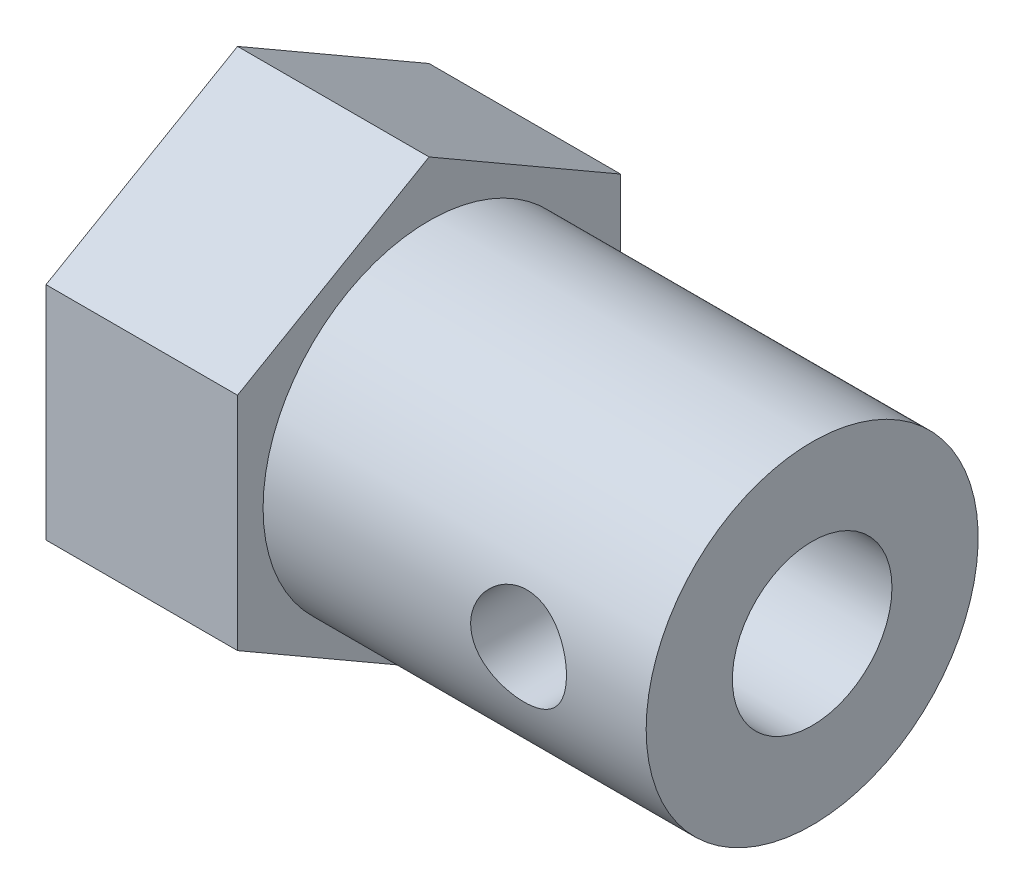
SolidWorks part; units mm, degrees
ref_plane "前视基准面" through (0, 0, 0) normal (0, 0, 1) x (1, 0, 0)
ref_plane "上视基准面" through (0, 0, 0) normal (0, 1, 0) x (1, 0, 0)
ref_plane "右视基准面" through (0, 0, 0) normal (1, 0, 0) x (0, 0, -1)
ref_plane "基准面4" through (-88, 0, 0) normal (-1, 0, 0) x (0, -1, 0)
sketch "草图1" plane through (-88, 0, 0) normal (-1, 0, 0) x (0, -1, 0)
  line L0 (76.9282, -33.5) -> (73.4641, -27.5)
  line L1 (73.4641, -27.5) -> (66.5359, -27.5)
  line L2 (66.5359, -27.5) -> (63.0718, -33.5)
  line L3 (63.0718, -33.5) -> (66.5359, -39.5)
  line L4 (66.5359, -39.5) -> (73.4641, -39.5)
  line L5 (73.4641, -39.5) -> (76.9282, -33.5)
extrude "凸台-拉伸1" add sketch "草图1" against normal blind 6
ref_plane "基准面5" through (0, 0, -33.5) normal (0, 0, -1) x (-1, 0, 0)
sketch "草图2" plane through (0, 0, -33.5) normal (0, 0, -1) x (-1, 0, 0)
  line L0 (70, -64.8) -> (70, -70)
  line L1 (70, -70) -> (82, -70)
  line L2 (82, -70) -> (82, -64.8)
  line L3 (82, -64.8) -> (70, -64.8)
  line L4 (70, -70) -> (82, -70) construction
revolve "旋转1" add sketch "草图2" angle 360 about L4
hole_wizard "M3.5 六角头机械螺钉的柱形沉头孔1" positions "草图4" profile "草图3" counterbore size "M3.5" standard "ANSI Metric"
sketch "草图4" plane through (-70, 0, 0) normal (1, 0, 0) x (0, 0, -1)
  point P0 (33.5, -70)
sketch "草图3" plane through (-70, -70, -33.5) normal (0, 1, 0) x (0, 0, -1)
  line L0 (0, 0) -> (0, 18)
  line L1 (0, 18) -> (2, 18)
  line L3 (2, 18) -> (2, 12)
  line L4 (2, 12) -> (2.5, 12)
  line L5 (2.5, 12) -> (2.5, 0)
  line L7 (2.5, 0) -> (0, 0)
  line L11 (0, -6.35) -> (0, 107.95) construction
  dimension "通孔孔直径" = 4
  dimension "通孔孔深度" = 18
  dimension "柱形沉头孔直径" = 5
  dimension "柱形沉头孔深度" = 12
ref_plane "基准面6" through (0, 0, -31.6223) normal (0, 0, -1) x (-1, 0, 0)
hole_wizard "Ø3.0 (3) 直径孔1" positions "草图6" profile "草图5" hole size "Ø3.0" standard "ANSI Metric"
sketch "草图6" plane through (0, 0, -31.6223) normal (0, 0, -1) x (-1, 0, 0)
  point P0 (74, -69.8495)
sketch "草图5" plane through (-74, -69.8495, -31.6223) normal (1, 0, 0) x (0, 1, 0)
  line L0 (0, 0) -> (0, 4.1223)
  line L1 (0, 4.1223) -> (1.5, 4.1223)
  line L2 (1.5, 4.1223) -> (1.5, 0)
  line L5 (1.5, 0) -> (0, 0)
  line L11 (0, -6.35) -> (0, 107.95) construction
  dimension "通孔孔直径" = 3
  dimension "通孔孔深度" = 4.1223
